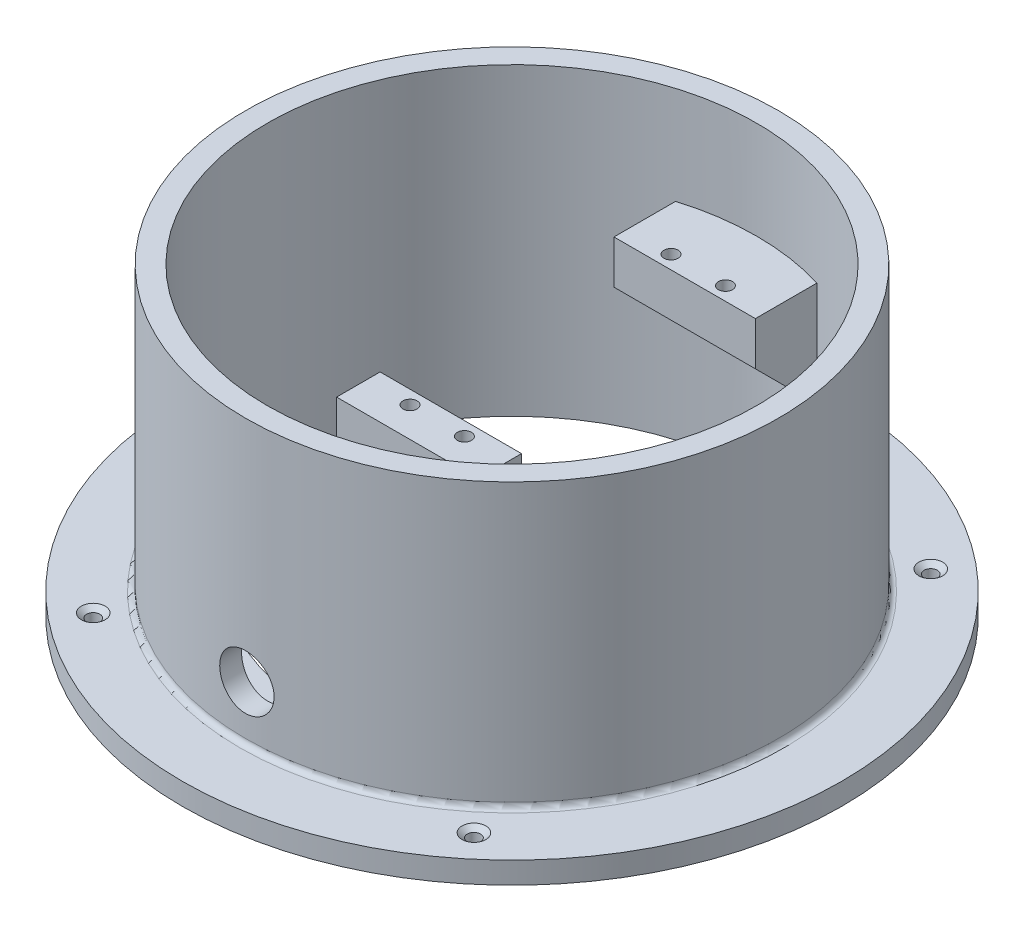
SolidWorks part; units mm, degrees
ref_plane "Front Plane" through (0, 0, 0) normal (0, 0, 1) x (1, 0, 0)
ref_plane "Top Plane" through (0, 0, 0) normal (0, 1, 0) x (1, 0, 0)
ref_plane "Right Plane" through (0, 0, 0) normal (1, 0, 0) x (0, 0, -1)
sketch "Sketch1" plane through (0, 0, 0) normal (0, 1, 0) x (1, 0, 0)
  circle A0 centre (0, 0) radius 60.625
  circle A1 centre (0, 0) radius 45
  dimension "D1" = 121.25
  dimension "D2" = 90
extrude "Boss-Extrude1" add sketch "Sketch1" along normal blind 4
sketch "Sketch2" plane through (0, 4, 0) normal (0, 1, 0) x (1, 0, 0)
  circle A0 centre (0, 0) radius 45 construction
  circle A1 centre (0, 0) radius 45
  circle A2 centre (0, 0) radius 49
  dimension "D1" = 4
extrude "Boss-Extrude2" add sketch "Sketch2" along normal blind 52
sketch "Sketch3" plane through (0, 0, 0) normal (1, 0, 0) x (0, 0, -1)
  line L0 (46.75, 38) -> (31.75, 38)
  line L1 (31.75, 38) -> (31.75, 30)
  line L2 (31.75, 30) -> (46.75, 30)
  line L3 (46.75, 30) -> (46.75, 38)
  line L4 (45, 56) -> (45, 0)
  line L5 (31.75, 30) -> (45, 16.75)
  line L6 (-45, 0) -> (45, 0) construction
  line L7 (-11.25, 38) -> (-19.25, 38)
  line L8 (-11.25, 38) -> (-11.25, 0)
  line L9 (-11.25, 0) -> (-19.25, 0)
  line L10 (-19.25, 38) -> (-19.25, 0)
  line L11 (-11.25, 38) -> (-19.25, 0) construction
  line L12 (-11.25, 0) -> (-19.25, 38) construction
  line L13 (45, 56) -> (-45, 56) construction
  point P8 (-15.25, 19)
  point P16 (-36.5954, 35.5381)
  point P17 (-20.4883, 35.9247)
  point P18 (-27.7043, 19.0444)
  point P19 (-31.1834, 38.2441)
  point P20 (-15.25, 38)
  point P24 (31.75, 34)
  dimension "D1" = 8
  dimension "D2" = 18
  dimension "D3" = 11.25
  dimension "D4" = 43
  dimension "D5" = 15
  dimension "D6" = 8
  dimension "D7" = 45
  dimension "D8" = 18
extrude "Boss-Extrude3" add sketch "Sketch3" along normal mid plane 26 contours L4 L0 L1 L2 | L2 L5 L4 | L7 L10 L9 L8
sketch "Sketch4" plane through (0, 0, 11.25) normal (0, 0, -1) x (-1, 0, 0)
  line L0 (13, 38) -> (-13, 38) construction
  line L1 (-5, 29) -> (5, 29)
  line L2 (-5, 29) -> (-5, 5)
  line L3 (-5, 5) -> (5, 5)
  line L4 (5, 29) -> (5, 5)
  line L5 (-5, 29) -> (5, 5) construction
  line L6 (-5, 5) -> (5, 29) construction
  line L8 (-60.625, 0) -> (60.625, 0) construction
  point P0 (0, 17)
  point P5 (10.3857, 34.2038)
  point P6 (10.1333, 35.8583)
  point P7 (0, 0)
  point P8 (0, 0)
  point P9 (0, 0)
  point P10 (11.1051, 5.3129)
  point P13 (-11.1613, 5.4258)
  point P16 (0, 0)
  point P17 (0, 0)
  point P18 (0, 0)
  point P21 (0, 0)
  point P22 (0, 0)
  point P23 (0, 0)
  point P24 (0, 0)
  point P25 (0, 0)
  point P26 (0, 0)
  point P27 (0, 0)
  dimension "D1" = 10
  dimension "D2" = 9
  dimension "D3" = 5
extrude "Cut-Extrude1" cut sketch "Sketch4" against normal blind 26
sketch "Sketch7" plane through (0, 0, 11.25) normal (0, 0, -1) x (-1, 0, 0)
  circle A2 centre (0, 14) radius 5
  dimension "D1" = 10
  dimension "D2" = 14
extrude "Cut-Extrude2" cut sketch "Sketch7" against normal blind 64
sketch "Sketch11" plane through (0, 38, 0) normal (0, 1, 0) x (1, 0, 0)
  line L0 (-5, 34.25) -> (5, 34.25)
  line L1 (-5, -13.75) -> (5, -13.75)
  line L2 (13, 31.75) -> (-13, 31.75) construction
  circle A0 centre (-5, 34.25) radius 1.3
  circle A1 centre (5, 34.25) radius 1.3
  circle A2 centre (-5, -13.75) radius 1.3
  circle A3 centre (5, -13.75) radius 1.3
  point P11 (0, 0)
  point P12 (0, 0)
  point P13 (0, 0)
  point P14 (0, 0)
  dimension "D1" = 2.6
  dimension "D5" = 2.5
  dimension "D2" = 10
  dimension "D3" = 10
  dimension "D4" = 5
  dimension "D6" = 48
extrude "Cut-Extrude5" cut sketch "Sketch11" against normal blind 7.2 contours A2 | A3 | A1 | A0
sketch "Sketch12" plane through (0, 0, 0) normal (0, -1, 0) x (1, 0, 0)
  line L0 (13, 11.25) -> (-13, 11.25) construction
  line L1 (13, 11.25) -> (-13, 11.25)
  line L2 (-37.2484, 25.2498) -> (-13, 11.25)
  line L3 (0, 0) -> (0, 32.9323) construction
  line L4 (37.2484, 25.2498) -> (13, 11.25)
  line L5 (-24.9065, 27.3618) -> (-19.5167, 24.25)
  line L7 (24.9065, 27.3618) -> (19.5167, 24.25)
  line L8 (19.5167, 24.25) -> (-19.5167, 24.25)
  line L9 (13, 19.25) -> (-13, 19.25) construction
  line L10 (-24.9065, 27.3618) -> (-10.8564, 19.25) construction
  line L11 (24.9065, 27.3618) -> (10.8564, 19.25) construction
  line L12 (10.8564, 19.25) -> (-10.8564, 19.25) construction
  arc A0 (24.9065, 27.3618) -> (-24.9065, 27.3618) centre (0, 0) ccw
  circle A3 centre (0, 0) radius 45 construction
  arc A4 (37.2484, 25.2498) -> (-37.2484, 25.2498) centre (0, 0) ccw
  point P14 (-22.3125, 24.25)
  dimension "D1" = 60
  dimension "D2" = 8
  dimension "D3" = 5
extrude "Boss-Extrude4" add sketch "Sketch12" against normal blind 4
sketch "Sketch13" plane through (0, 4, 0) normal (0, 1, 0) x (1, 0, 0)
  line L1 (-35, 42) -> (35, 42) construction
  line L2 (-35, 42) -> (-35, -42) construction
  line L3 (-35, -42) -> (35, -42) construction
  line L4 (35, 42) -> (35, -42) construction
  line L5 (-35, 42) -> (35, -42) construction
  line L6 (-35, -42) -> (35, 42) construction
  point P0 (0, 0)
  dimension "D1" = 84
  dimension "D2" = 70
hole_wizard "CSK for #2 Flat Head Machine Screw (100)1" positions "3DSketch1" profile "Sketch14" countersink size "#2" standard "ANSI Inch" end condition through all
sketch3d "3DSketch1"
  point P0 (35, 4, -42)
  point P3 (-35, 4, -42)
  point P6 (-35, 4, 42)
  point P9 (35, 4, 42)
sketch "Sketch14" plane through (35, 4, -42) normal (1, 0, 0) x (0, 0, 1)
  line L0 (0, 0) -> (0, 4)
  line L1 (0, 4) -> (1.2192, 4)
  line L2 (1.2192, 4) -> (1.2192, 0.8099)
  line L3 (1.2192, 0.8099) -> (2.1844, 0)
  line L5 (2.1844, 0) -> (0, 0)
  line L6 (-1.2192, 0.8099) -> (-2.1844, 0) construction
  line L11 (0, -6.35) -> (0, 107.95) construction
  dimension "Thru Hole Dia." = 2.4384
  dimension "Thru Hole Depth" = 4
  dimension "Near C'Sink Dia." = 4.3688
  dimension "Near C'Sink Angle" = 100
fillet "Fillet1" radius 1 1 edges at (0, 4, 49)
